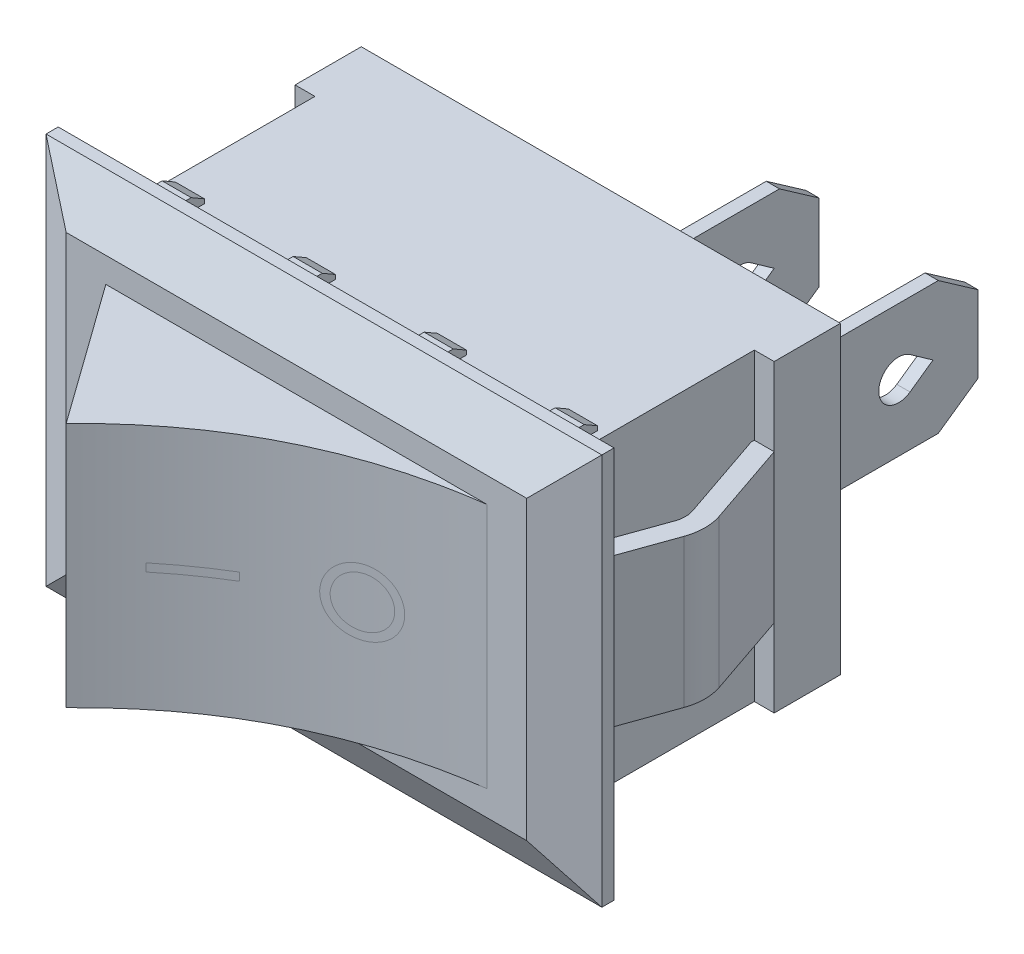
SolidWorks part; units mm, degrees
ref_plane "Front Plane" through (0, 0, 0) normal (0, 0, 1) x (1, 0, 0)
ref_plane "Top Plane" through (0, 0, 0) normal (0, 1, 0) x (1, 0, 0)
ref_plane "Right Plane" through (0, 0, 0) normal (1, 0, 0) x (0, 0, -1)
sketch "Sketch1" plane through (0, 0, 0) normal (0, 0, 1) x (1, 0, 0)
  line L1 (-8.3, -5.75) -> (8.3, -5.75)
  line L2 (-8.3, -5.75) -> (-8.3, 5.75)
  line L3 (-8.3, 5.75) -> (8.3, 5.75)
  line L4 (8.3, -5.75) -> (8.3, 5.75)
  line L5 (-8.3, -5.75) -> (8.3, 5.75) construction
  line L6 (-8.3, 5.75) -> (8.3, -5.75) construction
  point P0 (0, 0)
  dimension "D1" = 16.6
  dimension "D2" = 11.5
extrude "Boss-Extrude1" add sketch "Sketch1" along normal blind 10
sketch "Sketch2" plane through (0, 0, 10) normal (0, 0, 1) x (1, 0, 0)
  line L1 (-10.5, -7.4) -> (10.5, -7.4)
  line L2 (-10.5, -7.4) -> (-10.5, 7.4)
  line L3 (-10.5, 7.4) -> (10.5, 7.4)
  line L4 (10.5, -7.4) -> (10.5, 7.4)
  line L5 (-10.5, -7.4) -> (10.5, 7.4) construction
  line L6 (-10.5, 7.4) -> (10.5, -7.4) construction
  point P0 (0, 0)
  dimension "D1" = 14.8
  dimension "D2" = 21
extrude "Boss-Extrude2" add sketch "Sketch2" along normal blind 1.5
sketch "Sketch3" plane through (0, 0, 0) normal (0, 0, -1) x (-1, 0, 0)
  line L1 (-6.25, -2.5) -> (-5.75, -2.5)
  line L2 (-6.25, -2.5) -> (-6.25, 2.5)
  line L3 (-6.25, 2.5) -> (-5.75, 2.5)
  line L4 (-5.75, -2.5) -> (-5.75, 2.5)
  line L5 (-6.25, -2.5) -> (-5.75, 2.5) construction
  line L6 (-6.25, 2.5) -> (-5.75, -2.5) construction
  line L7 (-0.25, -2.5) -> (0.25, -2.5)
  line L8 (-0.25, -2.5) -> (-0.25, 2.5)
  line L9 (-0.25, 2.5) -> (0.25, 2.5)
  line L10 (0.25, -2.5) -> (0.25, 2.5)
  line L11 (-0.25, -2.5) -> (0.25, 2.5) construction
  line L12 (-0.25, 2.5) -> (0.25, -2.5) construction
  point P0 (-6, 0)
  point P5 (0, 0)
  dimension "D1" = 0.5
  dimension "D2" = 5
  dimension "D3" = 5
  dimension "D4" = 6
  dimension "D5" = 0.5
extrude "Boss-Extrude3" add sketch "Sketch3" along normal blind 8
sketch "Sketch4" plane through (6.25, 0, 0) normal (1, 0, 0) x (0, 0, -1)
  line L0 (2, 2.5) -> (2, 2.1)
  line L1 (8, 2.5) -> (0, 2.5) construction
  line L2 (2, 2.1) -> (2.5, 2.1)
  line L3 (2.5, 2.1) -> (2.5, 2.5)
  line L4 (0, 0) -> (8, 0) construction
  line L5 (8, 2.5) -> (8, -2.5) construction
  line L6 (0, 0.75) -> (0, -0.75)
  line L7 (2, 2.5) -> (2.5, 2.5)
  line L8 (6.5, 2.5) -> (8, 1.4497)
  line L9 (6.5, 2.5) -> (8, 2.5)
  line L10 (8, 2.5) -> (8, 1.4497)
  line L11 (5.4327, 0.6126) -> (6.3, 0)
  line L12 (5.4327, -0.6126) -> (6.3, 0)
  line L13 (8, -2.5) -> (8, -1.4497)
  line L14 (6.5, -2.5) -> (8, -2.5)
  line L15 (6.5, -2.5) -> (8, -1.4497)
  line L16 (2, -2.1) -> (2.5, -2.1)
  line L17 (2, -2.5) -> (2, -2.1)
  line L18 (2, -2.5) -> (2.5, -2.5)
  line L19 (2.5, -2.1) -> (2.5, -2.5)
  arc A0 (0, -0.75) -> (0, 0.75) centre (0, 0) ccw
  arc A1 (5.4327, 0.6126) -> (5.4327, -0.6126) centre (5, 0) ccw
  dimension "D1" = 1.5
  dimension "D7" = 1.5
  dimension "D2" = 0.5
  dimension "D3" = 0.4
  dimension "D4" = 2
  dimension "D5" = 35
  dimension "D6" = 1.5
  dimension "D8" = 5
  dimension "D9" = 1.3
extrude "Cut-Extrude1" cut sketch "Sketch4" against normal through all
sketch "Sketch5" plane through (0, 0, 0) normal (0, 1, 0) x (1, 0, 0)
  line L0 (-8.3, 0) -> (-9.05, 0)
  line L1 (-9.05, 0) -> (-9.05, -2.5)
  line L2 (-9.05, -2.5) -> (-8.3, -2.5)
  line L3 (-8.3, -10) -> (-8.3, 0) construction
  line L4 (-8.3, -2.5) -> (-8.3, 0)
  dimension "D1" = 2.5
  dimension "D2" = 0.75
extrude "Boss-Extrude4" add sketch "Sketch5" along normal up to surface and the other way up to surface up to face at (0, 5.75, 5) other way up to face at (0, -5.75, 5)
mirror "Mirror1" about plane through (0, 0, 0) normal (1, 0, 0) of "Boss-Extrude4"
sketch "Sketch6" plane through (0, 0, 0) normal (0, 1, 0) x (1, 0, 0)
  line L0 (-9.05, -2.5) -> (-10.1249, -5.6533)
  line L1 (-10.1156, -6.9707) -> (-9.0566, -9.9386)
  line L2 (0, -11.5) -> (0, 0) construction
  line L3 (10.5, -11.5) -> (-10.5, -11.5) construction
  line L4 (-8.3401, -2.742) -> (-9.4432, -5.9779)
  line L5 (-9.4385, -6.6366) -> (-8.3502, -9.6866)
  line L7 (-8.3, -10) -> (-8.3, -2.5) construction
  line L8 (-8.3401, -2.742) -> (-8.3, -2.6243)
  line L9 (-8.3, -2.6243) -> (-8.3, -2.5)
  line L10 (-8.3, -2.5) -> (-9.05, -2.5)
  line L11 (-9.0566, -9.9386) -> (-9.0347, -10)
  line L12 (10.5, -10) -> (-10.5, -10) construction
  line L13 (-9.0347, -10) -> (-8.3, -10)
  line L14 (-8.3, -10) -> (-8.3, -9.8274)
  line L15 (-8.3, -9.8274) -> (-8.3502, -9.6866)
  line L16 (8.3, -9.8274) -> (8.3502, -9.6866)
  line L17 (8.3, -10) -> (8.3, -9.8274)
  line L18 (9.0347, -10) -> (8.3, -10)
  line L19 (9.0566, -9.9386) -> (9.0347, -10)
  line L20 (8.3, -2.5) -> (9.05, -2.5)
  line L21 (8.3, -2.6243) -> (8.3, -2.5)
  line L22 (8.3401, -2.742) -> (8.3, -2.6243)
  line L23 (9.4385, -6.6366) -> (8.3502, -9.6866)
  line L24 (8.3401, -2.742) -> (9.4432, -5.9779)
  line L25 (10.1156, -6.9707) -> (9.0566, -9.9386)
  line L26 (9.05, -2.5) -> (10.1249, -5.6533)
  line L27 (-10.35, -6.3137) -> (-9.0566, -9.9386) construction
  line L28 (-9.05, -2.5) -> (-10.35, -6.3137) construction
  line L29 (-9.5557, -6.308) -> (-8.3502, -9.6866) construction
  line L30 (-8.3401, -2.742) -> (-9.5557, -6.308) construction
  arc A0 (-10.1156, -6.9707) -> (-10.1249, -5.6533) centre (-8.2319, -6.2986) cw
  arc A1 (-9.4385, -6.6366) -> (-9.4432, -5.9779) centre (-8.4966, -6.3005) cw
  arc A2 (9.4385, -6.6366) -> (9.4432, -5.9779) centre (8.4966, -6.3005) ccw
  arc A3 (10.1156, -6.9707) -> (10.1249, -5.6533) centre (8.2319, -6.2986) ccw
  point P37 (-10.35, -6.3137)
  point P41 (-9.5557, -6.308)
  point P44 (9.5557, -6.308)
  point P47 (10.35, -6.3137)
  dimension "D3" = 2
  dimension "D4" = 1
  dimension "D5" = 1
  dimension "D6" = 2
  dimension "D1" = 10.35
  dimension "D2" = 0.75
extrude "Boss-Extrude5" add sketch "Sketch6" along normal blind 2.8 and the other way blind 2.8
chamfer "Chamfer1" distance 1.8 angle 30 4 edges at (-10.5, 0, 11.5) (0, -7.4, 11.5) (10.5, 0, 11.5) (0, 7.4, 11.5)
sketch "Sketch7" plane through (0, 0, 0) normal (0, 1, 0) x (1, 0, 0)
  line L0 (-7.2, -11.5) -> (-3.3987, -16.8)
  line L1 (-8.7, -11.5) -> (8.7, -11.5) construction
  line L2 (-9.05, 0) -> (9.05, 0) construction
  line L3 (-7.2, -11.5) -> (7.2, -11.5)
  spline S0 degree 2 poles (-3.3987, -16.8) (0.9274, -12.3348) (7.2, -11.5) knots 0 0 0 1 1 1
  dimension "D1" = 16.8
  dimension "D2" = 1.5
  dimension "D3" = 1.5
extrude "Boss-Extrude6" add sketch "Sketch7" along normal mid plane 9.3
ref_plane "Plane1" through (6.0406, 0, 12.0798) normal (0.4473, 0, 0.8944) x (0.8944, 0, -0.4473)
sketch "Sketch8" plane through (6.0406, 0, 12.0798) normal (0.4473, 0, 0.8944) x (0.8944, 0, -0.4473)
  line L1 (-8.5, -0.15) -> (-6, -0.15)
  line L2 (-8.5, -0.15) -> (-8.5, 0.15)
  line L3 (-8.5, 0.15) -> (-6, 0.15)
  line L4 (-6, -0.15) -> (-6, 0.15)
  line L5 (-8.5, -0.15) -> (-6, 0.15) construction
  line L6 (-8.5, 0.15) -> (-6, -0.15) construction
  circle A0 centre (-2.5, 0) radius 1.25
  circle A1 centre (-2.5, 0) radius 0.95
  point P0 (-7.25, 0)
  dimension "D4" = 0.3
  dimension "D6" = 2.5
  dimension "D1" = 0.3
  dimension "D2" = 2.5
  dimension "D3" = 6
  dimension "D5" = 2.5
split line "Split Line1"
sketch "Sketch9" plane through (0, 0, 10) normal (0, 0, -1) x (-1, 0, 0)
  line L0 (-9.05, 5.75) -> (9.05, 5.75) construction
  line L1 (-7.975, 5.75) -> (-6.875, 5.75)
  line L2 (-7.975, 5.75) -> (-7.975, 6.2)
  line L3 (-7.975, 6.2) -> (-6.875, 6.2)
  line L4 (-6.875, 5.75) -> (-6.875, 6.2)
  line L5 (-8.3, 5.75) -> (8.3, 5.75) construction
  line L7 (0, 0) -> (0, 6.2) construction
  line L8 (-3.025, 5.75) -> (-1.925, 5.75)
  line L9 (-3.025, 5.75) -> (-3.025, 6.2)
  line L10 (-3.025, 6.2) -> (-1.925, 6.2)
  line L11 (-1.925, 5.75) -> (-1.925, 6.2)
  line L12 (0, 0) -> (-7.7156, 0) construction
  line L13 (1.925, 5.75) -> (1.925, 6.2)
  line L14 (3.025, 6.2) -> (1.925, 6.2)
  line L15 (3.025, 5.75) -> (3.025, 6.2)
  line L16 (3.025, 5.75) -> (1.925, 5.75)
  line L17 (6.875, 5.75) -> (6.875, 6.2)
  line L18 (7.975, 6.2) -> (6.875, 6.2)
  line L19 (7.975, 5.75) -> (7.975, 6.2)
  line L20 (7.975, 5.75) -> (6.875, 5.75)
  line L21 (7.975, -5.75) -> (6.875, -5.75)
  line L22 (7.975, -5.75) -> (7.975, -6.2)
  line L23 (7.975, -6.2) -> (6.875, -6.2)
  line L24 (6.875, -5.75) -> (6.875, -6.2)
  line L25 (3.025, -5.75) -> (1.925, -5.75)
  line L26 (3.025, -5.75) -> (3.025, -6.2)
  line L27 (3.025, -6.2) -> (1.925, -6.2)
  line L28 (1.925, -5.75) -> (1.925, -6.2)
  line L29 (-1.925, -5.75) -> (-1.925, -6.2)
  line L30 (-3.025, -6.2) -> (-1.925, -6.2)
  line L31 (-3.025, -5.75) -> (-3.025, -6.2)
  line L32 (-3.025, -5.75) -> (-1.925, -5.75)
  line L33 (-6.875, -5.75) -> (-6.875, -6.2)
  line L34 (-7.975, -6.2) -> (-6.875, -6.2)
  line L35 (-7.975, -5.75) -> (-7.975, -6.2)
  line L36 (-7.975, -5.75) -> (-6.875, -5.75)
  dimension "D1" = 1.1
  dimension "D2" = 0.45
  dimension "D3" = 1.925
  dimension "D4" = 1.1
  dimension "D5" = 3.85
extrude "Boss-Extrude7" add sketch "Sketch9" along normal blind 1.9
chamfer "Chamfer2" distance 0.5 angle 30 8 edges at (-7.425, -6.2, 8.1) (-2.475, -6.2, 8.1) (2.475, -6.2, 8.1) (7.425, -6.2, 8.1) (-7.425, 6.2, 8.1) (-2.475, 6.2, 8.1) (2.475, 6.2, 8.1) (7.425, 6.2, 8.1)
scale "Scale2" bodies to scale 111 scale about centroid uniform scaling yes scale factor 0.7
